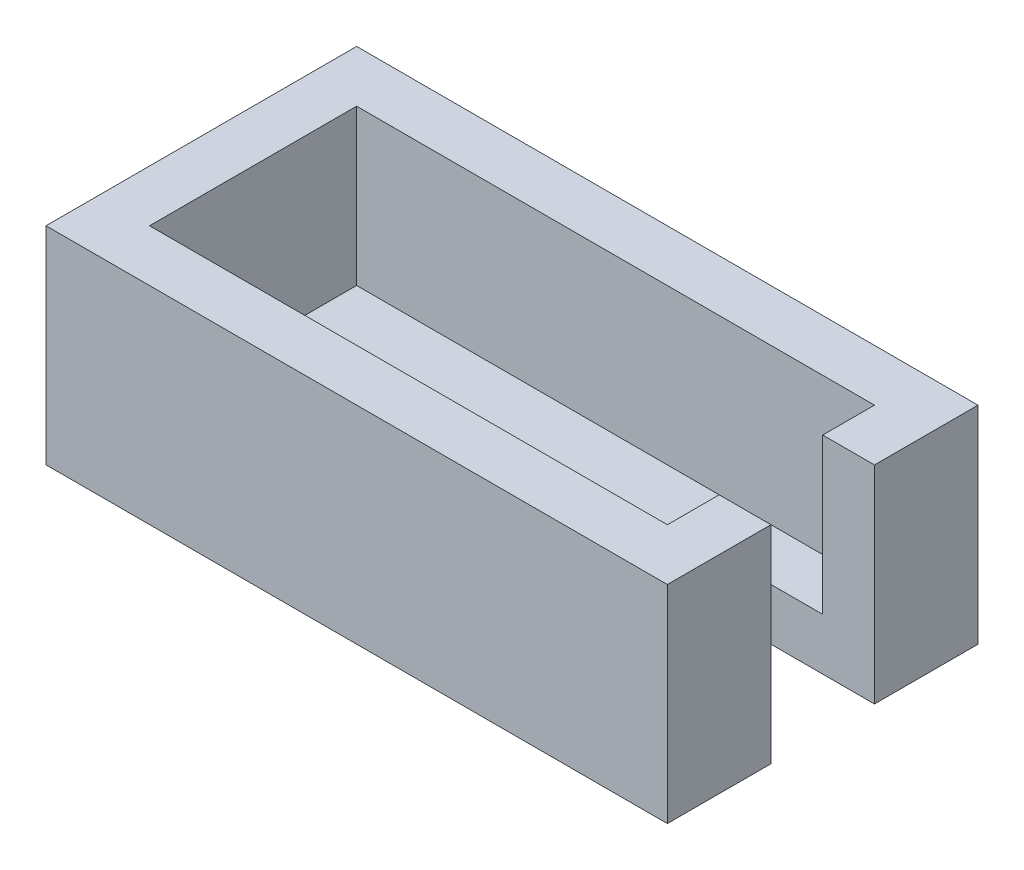
SolidWorks part; units mm, degrees
ref_plane "Front Plane" through (0, 0, 0) normal (0, 0, 1) x (1, 0, 0)
ref_plane "Top Plane" through (0, 0, 0) normal (0, 1, 0) x (1, 0, 0)
ref_plane "Right Plane" through (0, 0, 0) normal (1, 0, 0) x (0, 0, -1)
sketch "Sketch1" plane through (0, 0, 0) normal (0, 0, 1) x (1, 0, 0)
  line L1 (0, 0) -> (304.8, 0)
  line L2 (0, 0) -> (0, 101.6)
  line L3 (0, 101.6) -> (304.8, 101.6)
  line L4 (304.8, 0) -> (304.8, 101.6)
  dimension "D1" = 101.6
  dimension "D2" = 304.8
sketch "Sketch3" plane through (0, 0, 0) normal (0, 1, 0) x (1, 0, 0)
  line L0 (304.8987, 152.4261) -> (304.8987, 101.6261)
  line L1 (0, 0) -> (304.8987, 0)
  line L2 (0, 0) -> (0, 152.4261)
  line L3 (0, 152.4261) -> (304.8987, 152.4261)
  line L4 (304.8987, 0) -> (304.8987, 152.4261)
  line L5 (304.8987, 101.6261) -> (304.8987, 50.8261)
  line L6 (304.8987, 50.8261) -> (241.3987, 50.8261)
  line L7 (241.3987, 50.8261) -> (241.3987, 101.6261)
  line L8 (241.3987, 101.6261) -> (304.8987, 101.6261)
extrude "Boss-Extrude1" add sketch "Sketch3" along normal blind 101.6 contours L3 L2 L1 L4
sketch "Sketch4" plane through (0, 0, 0) normal (0, 1, 0) x (1, 0, 0)
  line L0 (304.8987, 152.4261) -> (304.8987, 101.6261)
  line L1 (304.8987, 0) -> (304.8987, 152.4261) construction
  line L2 (304.8987, 101.6261) -> (304.8987, 50.8261)
  line L3 (304.8987, 50.8261) -> (241.3987, 50.8261)
  line L4 (241.3987, 50.8261) -> (241.3987, 101.6261)
  line L5 (241.3987, 101.6261) -> (304.8987, 101.6261)
extrude "Cut-Extrude1" cut sketch "Sketch4" along normal blind 147.32 contours L5 L4 L3 L2
sketch "Sketch5" plane through (0, 101.6, 0) normal (0, 1, 0) x (1, 0, 0)
  line L0 (0, 152.4261) -> (304.8987, 152.4261) construction
  line L1 (25.4, 127.0261) -> (279.4987, 127.0261)
  line L2 (25.4, 127.0261) -> (25.4, 25.4)
  line L3 (25.4, 25.4) -> (279.4987, 25.4)
  line L4 (279.4987, 127.0261) -> (279.4987, 25.4)
  line L5 (0, 0) -> (304.8, 0) construction
  line L6 (0, 0) -> (0, 152.4261) construction
  line L7 (304.8987, 101.6261) -> (304.8987, 152.4261) construction
  circle A0 centre (76.2, 76.2261) radius 19.05
  circle A1 centre (133.35, 76.2261) radius 19.05
  circle A2 centre (190.5, 76.2261) radius 19.05
  dimension "D6" = 57.15
  dimension "D7" = 57.15
  dimension "D1" = 25.4
  dimension "D2" = 25.4
  dimension "D3" = 25.4
  dimension "D4" = 25.4
  dimension "D5" = 50.8
extrude "Cut-Extrude2" cut sketch "Sketch5" against normal blind 76.2
sketch "Sketch7" plane through (0, 0, 0) normal (0, 1, 0) x (1, 0, 0)
  circle A0 centre (76.2, 76.2261) radius 19.05
  circle A1 centre (133.35, 76.2261) radius 19.05
  circle A2 centre (190.5, 76.2261) radius 19.05
extrude "Cut-Extrude3" cut sketch "Sketch7" along normal blind 138.938
